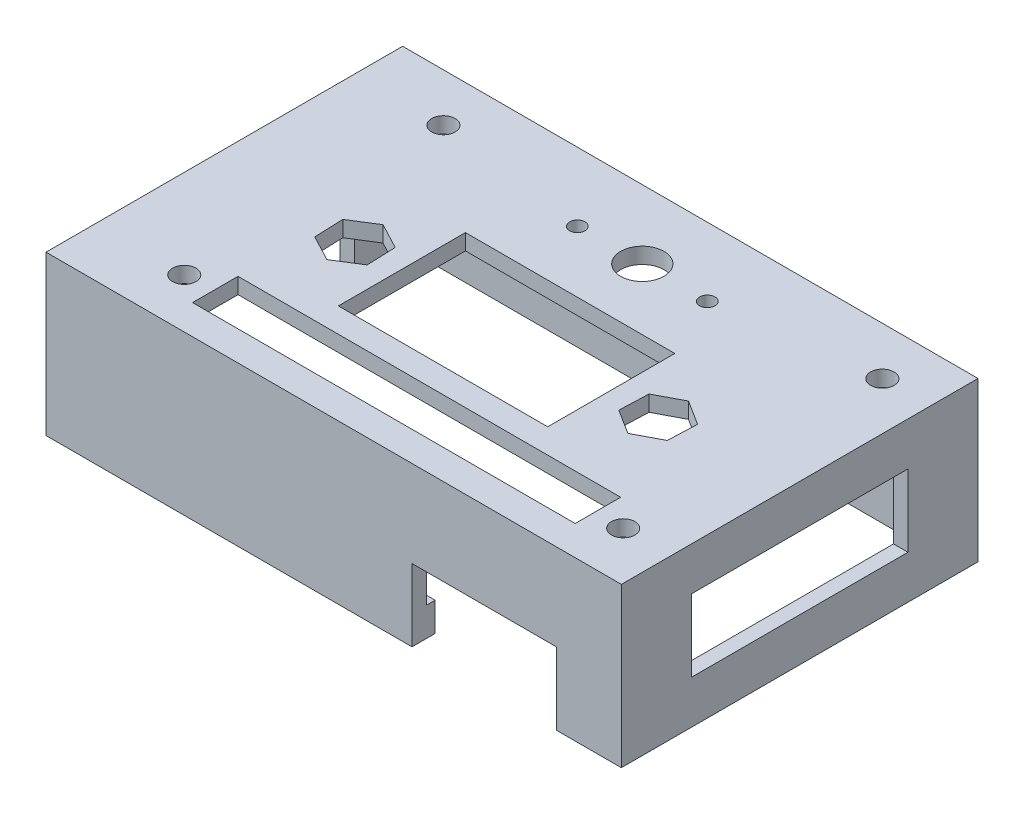
SolidWorks part; units mm, degrees
ref_plane "前视基准面" through (0, 0, 0) normal (0, 0, 1) x (1, 0, 0)
ref_plane "上视基准面" through (0, 0, 0) normal (0, 1, 0) x (1, 0, 0)
ref_plane "右视基准面" through (0, 0, 0) normal (1, 0, 0) x (0, 0, -1)
other "Configuration Table"
sketch "草图1" plane through (0, 0, 0) normal (0, 1, 0) x (1, 0, 0)
  line L1 (-35, 22.7) -> (35, 22.7)
  line L2 (-35, 22.7) -> (-35, -22.7)
  line L3 (-35, -22.7) -> (35, -22.7)
  line L4 (35, 22.7) -> (35, -22.7)
  line L5 (-35, 22.7) -> (35, -22.7) construction
  line L6 (-35, -22.7) -> (35, 22.7) construction
  point P0 (0, 0)
  dimension "D1" = 70
  dimension "D2" = 45.4
extrude "凸台-拉伸1" add sketch "草图1" along normal blind 2.2
sketch "草图2" plane through (0, 2.2, 0) normal (0, 1, 0) x (1, 0, 0)
  line L0 (0, 0) -> (0, 28.7415) construction
  line L1 (0, 0) -> (-42.7208, 0) construction
  line L2 (35, 22.7) -> (-35, 22.7) construction
  line L3 (-30.4, 18.05) -> (-30.4, -17.85) construction
  circle A0 centre (-30.4, 18.05) radius 1.62
  circle A1 centre (-30.4, -17.85) radius 1.62
  circle A2 centre (30.4, -17.85) radius 1.62
  circle A3 centre (30.4, 18.05) radius 1.62
  dimension "D3" = 3.24
  dimension "D5" = 3.24
  dimension "D1" = 30.4
  dimension "D2" = 4.65
  dimension "D4" = 35.9
extrude "切除-拉伸1" cut sketch "草图2" against normal blind 12.2
sketch "草图3" plane through (0, 2.2, 0) normal (0, 1, 0) x (1, 0, 0)
  line L0 (0, 0) -> (48.8344, 0) construction
  line L1 (0, 0) -> (0, 28.2941) construction
  line L2 (13, 22.7) -> (13, 6.7) construction
  line L3 (35, 22.7) -> (-35, 22.7) construction
  line L9 (13, 6.7) -> (-16, 6.7)
  line L10 (13, 6.7) -> (13, -10.9)
  line L11 (13, -10.9) -> (-16, -10.9)
  line L12 (-16, 6.7) -> (-16, -10.9)
  dimension "D1" = 16
  dimension "D2" = 13
  dimension "D3" = 29
  dimension "D4" = 33.6
extrude "切除-拉伸2" cut sketch "草图3" against normal blind 12.2
sketch "草图5" plane through (0, 2.2, 0) normal (0, 1, 0) x (1, 0, 0)
  line L0 (0, 0) -> (0, 28.7415) construction
  line L1 (9, 22.7) -> (9, 15.2) construction
  line L2 (35, 22.7) -> (-35, 22.7) construction
  circle A0 centre (9, 15.2) radius 1.07
  circle A1 centre (-9, 15.2) radius 1.07
  circle A2 centre (0, 15.2) radius 3
  dimension "D3" = 2.14
  dimension "D4" = 6
  dimension "D1" = 7.5
  dimension "D2" = 9
  dimension "D5" = 7.5
extrude "切除-拉伸4" cut sketch "草图5" against normal blind 12.2
sketch "草图6" plane through (0, 2.2, 0) normal (0, 1, 0) x (1, 0, 0)
  line L0 (26.5, 22.7) -> (26.5, -14.3) construction
  line L1 (35, 22.7) -> (-35, 22.7) construction
  line L2 (0, 0) -> (0, 29.7107) construction
  line L4 (26.5, -14.3) -> (-26.5, -14.3)
  line L5 (26.5, -14.3) -> (26.5, -20.6)
  line L6 (26.5, -20.6) -> (-26.5, -20.6)
  line L7 (-26.5, -14.3) -> (-26.5, -20.6)
  dimension "D1" = 37
  dimension "D2" = 26.5
  dimension "D3" = 53
  dimension "D4" = 43.3
extrude "切除-拉伸5" cut sketch "草图6" against normal blind 12.2
sketch "草图7" plane through (0, 2.2, 0) normal (0, 1, 0) x (1, 0, 0)
  line L1 (35, 22.7) -> (-40.7, 22.7)
  line L2 (35, 22.7) -> (35, 24.7)
  line L3 (35, 24.7) -> (-40.7, 24.7)
  line L4 (-40.7, 22.7) -> (-40.7, 24.7)
  dimension "D1" = 2
  dimension "D2" = 75.7
extrude "凸台-拉伸3" add sketch "草图7" against normal blind 22
sketch "草图8" plane through (0, 2.2, 0) normal (0, 1, 0) x (1, 0, 0)
  line L0 (-35, -22.7) -> (35, -22.7) construction
  line L1 (35, 24.7) -> (37, 24.7)
  line L2 (35, 24.7) -> (35, -24.7)
  line L3 (35, -24.7) -> (37, -24.7)
  line L4 (37, 24.7) -> (37, -24.7)
  dimension "D1" = 2
  dimension "D2" = 2
extrude "凸台-拉伸4" add sketch "草图8" against normal blind 22
sketch "草图9" plane through (0, 2.2, 0) normal (0, 1, 0) x (1, 0, 0)
  line L1 (35, -24.7) -> (-40.7, -24.7)
  line L2 (35, -24.7) -> (35, -22.7)
  line L3 (35, -22.7) -> (-40.7, -22.7)
  line L4 (-40.7, -24.7) -> (-40.7, -22.7)
  dimension "D1" = 2
  dimension "D2" = 75.7
extrude "凸台-拉伸5" add sketch "草图9" against normal blind 22
sketch "草图10" plane through (0, 2.2, 0) normal (0, 1, 0) x (1, 0, 0)
  line L1 (-35, 22.7) -> (-40.7, 22.7)
  line L2 (-35, 22.7) -> (-35, -22.7)
  line L3 (-35, -22.7) -> (-40.7, -22.7)
  line L4 (-40.7, 22.7) -> (-40.7, -22.7)
extrude "凸台-拉伸6" add sketch "草图10" against normal blind 2.2
sketch "草图11" plane through (0, 2.2, 0) normal (0, 1, 0) x (1, 0, 0)
  line L0 (-40.7, -24.7) -> (37, -24.7) construction
  line L1 (-40.7, 24.7) -> (-42.7, 24.7)
  line L2 (-40.7, 24.7) -> (-40.7, -24.7)
  line L3 (-40.7, -24.7) -> (-42.7, -24.7)
  line L4 (-42.7, 24.7) -> (-42.7, -24.7)
  dimension "D1" = 0
  dimension "D2" = 2
extrude "凸台-拉伸7" add sketch "草图11" against normal blind 22
sketch "草图12" plane through (0, 0, 24.7) normal (0, 0, 1) x (1, 0, 0)
  line L0 (-42.7, -19.8) -> (37, -19.8) construction
  line L1 (28, -19.8) -> (8, -19.8)
  line L2 (28, -19.8) -> (28, -9.8)
  line L3 (28, -9.8) -> (8, -9.8)
  line L4 (8, -19.8) -> (8, -9.8)
  line L5 (37, -19.8) -> (37, 2.2) construction
  dimension "D1" = 10
  dimension "D2" = 9
  dimension "D3" = 20
extrude "切除-拉伸6" cut sketch "草图12" against normal blind 22
sketch "草图13" plane through (-42.7, 0, 0) normal (-1, 0, 0) x (0, 0, 1)
  line L0 (0, 0) -> (0, -28.8951) construction
  line L1 (-24.7, -19.8) -> (24.7, -19.8) construction
  line L2 (16, -19.8) -> (-16, -19.8)
  line L3 (16, -19.8) -> (16, -13.8)
  line L4 (16, -13.8) -> (-16, -13.8)
  line L5 (-16, -19.8) -> (-16, -13.8)
  dimension "D1" = 16
  dimension "16" = 16
  dimension "D3" = 6
extrude "切除-拉伸7" cut sketch "草图13" against normal blind 22
sketch "草图14" plane through (37, 0, 0) normal (1, 0, 0) x (0, 0, -1)
  line L0 (0, 0) -> (0, -24.1017) construction
  line L6 (-24.7, 2.2) -> (24.7, 2.2) construction
  line L7 (-15, -3.8) -> (15, -3.8)
  line L8 (-15, -3.8) -> (-15, -13.8)
  line L9 (-15, -13.8) -> (15, -13.8)
  line L10 (15, -3.8) -> (15, -13.8)
  line L11 (-15, -3.8) -> (15, -13.8) construction
  line L12 (-15, -13.8) -> (15, -3.8) construction
  point P3 (0, -8.8)
  dimension "D1" = 30
  dimension "D2" = 11
  dimension "D3" = 10
extrude "切除-拉伸8" cut sketch "草图14" against normal blind 22
sketch "草图16" plane through (0, 0, -24.7) normal (0, 0, -1) x (-1, 0, 0)
  line L0 (-37, 2.2) -> (42.7, -19.8) construction
  line L1 (42.7, 2.2) -> (-37, -19.8) construction
  line L2 (2.85, -8.8) -> (2.85, 15.2923) construction
  line L3 (-37, 2.2) -> (42.7, 2.2) construction
  line L4 (-32.15, -0.8) -> (37.85, -0.8)
  line L5 (-32.15, -0.8) -> (-32.15, -10.8)
  line L6 (-32.15, -10.8) -> (37.85, -10.8)
  line L7 (37.85, -0.8) -> (37.85, -10.8)
  line L8 (-32.15, -0.8) -> (37.85, -10.8) construction
  line L9 (-32.15, -10.8) -> (37.85, -0.8) construction
  point P10 (2.85, -5.8)
  dimension "D1" = 8
  dimension "D2" = 10
  dimension "D3" = 70
extrude "切除-拉伸9" cut sketch "草图16" against normal blind 22
sketch "草图17" plane through (0, 0, 22.7) normal (0, 0, -1) x (-1, 0, 0)
  line L0 (40.7, -19.8) -> (40.7, 0) construction
  line L1 (-8, -19.8) -> (40.7, -19.8)
  line L2 (-8, -19.8) -> (-8, -15.8)
  line L3 (-8, -15.8) -> (40.7, -15.8)
  line L4 (40.7, -19.8) -> (40.7, -15.8)
  dimension "D1" = 4
extrude "凸台-拉伸8" add sketch "草图17" along normal blind 1.2
sketch "草图18" plane through (0, 0, 22.7) normal (0, 0, -1) x (-1, 0, 0)
  line L0 (-35, -19.8) -> (-35, 0) construction
  line L1 (-28, -19.8) -> (-35, -19.8)
  line L2 (-28, -19.8) -> (-28, -15.8)
  line L3 (-28, -15.8) -> (-35, -15.8)
  line L4 (-35, -19.8) -> (-35, -15.8)
  dimension "D1" = 4
extrude "凸台-拉伸9" add sketch "草图18" along normal blind 1.2
sketch "草图19" plane through (0, 2.2, 0) normal (0, 1, 0) x (1, 0, 0)
  line L0 (-16, 6.7) -> (13, -10.9) construction
  line L1 (13, 6.7) -> (-16, -10.9) construction
  line L2 (-1.5, -2.1) -> (-22.5, -2.1) construction
  line L3 (-1.5, -2.1) -> (-1.5, -30.8743) construction
  line L4 (22.9195, -4.2542) -> (19.3442, -6.1384)
  line L5 (-19.0805, 0.0542) -> (-22.6558, 1.9384)
  line L6 (-22.6558, 1.9384) -> (-26.0753, -0.2157)
  line L7 (-26.0753, -0.2157) -> (-25.9195, -4.2542)
  line L8 (-25.9195, -4.2542) -> (-22.3442, -6.1384)
  line L9 (-22.3442, -6.1384) -> (-18.9247, -3.9843)
  line L10 (-18.9247, -3.9843) -> (-19.0805, 0.0542)
  line L11 (19.3442, -6.1384) -> (15.9247, -3.9843)
  line L12 (15.9247, -3.9843) -> (16.0805, 0.0542)
  line L13 (16.0805, 0.0542) -> (19.6558, 1.9384)
  line L14 (19.6558, 1.9384) -> (23.0753, -0.2157)
  line L15 (23.0753, -0.2157) -> (22.9195, -4.2542)
  circle A0 centre (-22.5, -2.1) radius 3.5 construction
  dimension "D3" = 7
  dimension "D1" = 21
extrude "切除-拉伸10" cut sketch "草图19" against normal blind 11.2
